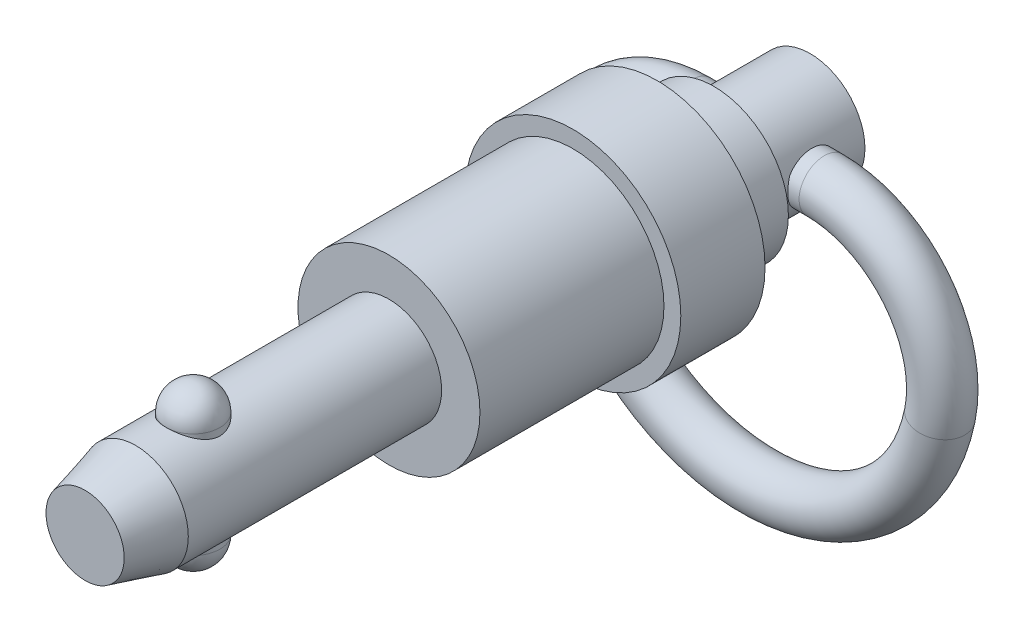
SolidWorks part; units mm, degrees
material "Cast Alloy Steel"
ref_plane "Front Plane" through (0, 0, 0) normal (0, 0, 1) x (1, 0, 0)
ref_plane "Top Plane" through (0, 0, 0) normal (0, 1, 0) x (1, 0, 0)
ref_plane "Right Plane" through (0, 0, 0) normal (1, 0, 0) x (0, 0, -1)
sketch "Sketch1" plane through (0, 0, 0) normal (1, 0, 0) x (0, 0, -1)
  line L0 (0, 0) -> (0, 3.125)
  line L1 (0, 3.125) -> (18.034, 3.125)
  line L2 (18.034, 3.125) -> (18.034, 5.4)
  line L3 (18.034, 5.4) -> (28.956, 5.4)
  line L4 (28.956, 5.4) -> (28.956, 6.4)
  line L5 (28.956, 6.4) -> (33.956, 6.4)
  line L6 (33.956, 6.4) -> (33.956, 4.4164)
  line L7 (33.956, 4.4164) -> (37.3248, 4.4164)
  line L8 (37.3248, 4.4164) -> (37.3248, 3.25)
  line L9 (37.3248, 3.25) -> (43.034, 3.25)
  line L10 (43.034, 3.25) -> (43.034, 0)
  line L11 (43.034, 0) -> (0, 0)
  line L12 (-6.2543, 0) -> (0, 0) construction
  dimension "D1" = 6.25
  dimension "D2" = 10.8
  dimension "D3" = 6.5
  dimension "D5" = 10.922
  dimension "D6" = 18.034
  dimension "D7" = 25
revolve "Revolve1" add sketch "Sketch1" angle 360 about L12
chamfer "Chamfer1" distance 3 angle 15 1 edges at (3.125, 0, 0)
sketch "Sketch2" plane through (0, 0, 0) normal (1, 0, 0) x (0, 0, -1)
  line L0 (6.415, 3.125) -> (6.415, -3.125) construction
  line L1 (8, 3.125) -> (8, -3.125)
  line L3 (18.034, 3.125) -> (3, 3.125) construction
  line L4 (0, 0) -> (6.415, 0) construction
  line L5 (6.415, 4.71) -> (6.415, -4.71)
  arc A0 (8, 3.125) -> (6.415, 4.71) centre (6.415, 3.125) ccw
  arc A1 (6.415, -4.71) -> (8, -3.125) centre (6.415, -3.125) ccw
  point P2 (7.27, 0)
  point P7 (6.415, 4.71)
  point P8 (6.415, -4.71)
  dimension "D1" = 8
  dimension "D2" = 9.42
revolve "Revolve2" add sketch "Sketch2" angle 360 about L5
ref_plane "Plane1" through (0, 0, -39.956) normal (0, 0, -1) x (-1, 0, 0)
sketch "Sketch3" plane through (0, 42, -39.956) normal (0, 0, -1) x (1, 0, 0)
  line L0 (-3.9192, 42) -> (0, 42)
  line L1 (3.9192, 42) -> (3.1669, 42)
  line L4 (9.0863, 42) -> (3.1669, 42) construction
  line L5 (-9.8468, 40.5) -> (0, 40.5) construction
  line L6 (9.8468, 40.5) -> (3.1669, 40.5) construction
  line L7 (-9.0863, 42) -> (0, 42) construction
  arc A0 (-10.7778, 50.4) -> (10.7778, 50.4) centre (0, 48.2) cw
  arc A1 (-9.8468, 40.5) -> (9.8468, 40.5) centre (0, 48.2) cw construction
  arc A2 (-9.0863, 42) -> (9.0863, 42) centre (0, 48.2) cw construction
  arc A3 (10.7778, 50.4) -> (3.9192, 42) centre (3.9192, 49) cw
  arc A4 (-10.7778, 50.4) -> (-3.9192, 42) centre (-3.9192, 49) ccw
  point P1 (-6.4, 42)
  point P3 (0, 60.7)
  dimension "D1" = 1.5
  dimension "D3" = 12.5
  dimension "D4" = 7
  dimension "D2" = 6.2
sketch "Sketch4" plane through (0, 0, 0) normal (1, 0, 0) x (0, 0, -1)
  circle A0 centre (39.956, 0) radius 1.5
  dimension "D1" = 3
sweep "Sweep2" add profiles "Sketch4" path "Sketch3"
